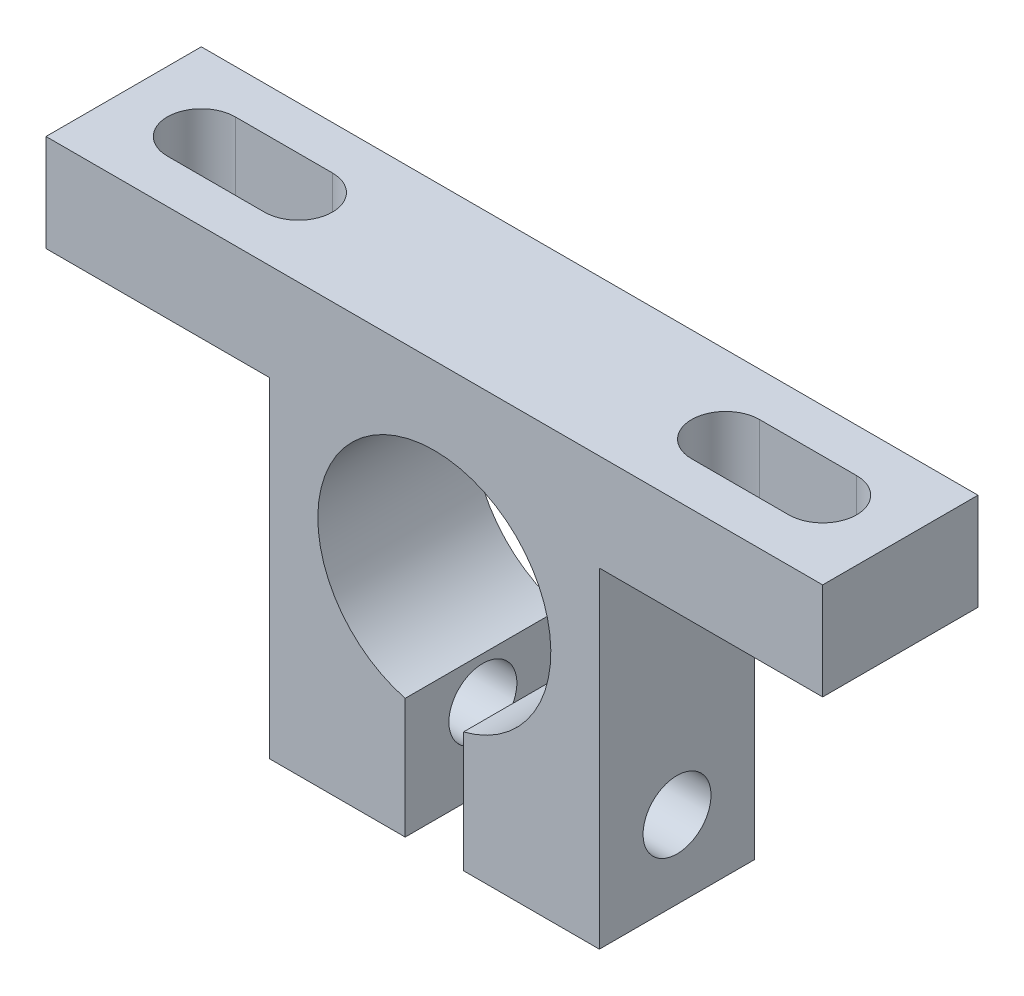
SolidWorks part; units mm, degrees
ref_plane "前视基准面" through (0, 0, 0) normal (0, 0, 1) x (1, 0, 0)
ref_plane "上视基准面" through (0, 0, 0) normal (0, 1, 0) x (1, 0, 0)
ref_plane "右视基准面" through (0, 0, 0) normal (1, 0, 0) x (0, 0, -1)
sketch "草图1" plane through (0, 0, 0) normal (0, 0, 1) x (1, 0, 0)
  line L0 (0, 0) -> (0, 11.4885) construction
  line L1 (34.9259, 10) -> (51.6493, 10) construction
  line L2 (20, 10) -> (-20, 10)
  line L3 (-20, 10) -> (-20, 5)
  line L4 (-20, 5) -> (-8.5, 5)
  line L5 (-8.5, 5) -> (-8.5, -12)
  line L6 (-8.5, -12) -> (-1.5, -12)
  line L7 (-1.5, -12) -> (-1.5, -5.8095)
  line L8 (1.5, -12) -> (1.5, -5.8095)
  line L9 (8.5, -12) -> (1.5, -12)
  line L10 (8.5, 5) -> (8.5, -12)
  line L11 (20, 5) -> (8.5, 5)
  line L12 (20, 10) -> (20, 5)
  arc A0 (1.5, -5.8095) -> (-1.5, -5.8095) centre (0, 0) ccw
  point P4 (0, 10)
  point P10 (0, -12)
  point P12 (-8.5, -12)
  point P16 (-1.5, -12)
  point P23 (0, 10)
  dimension "D1" = 10
  dimension "D5" = 6
  dimension "D2" = 22
  dimension "D3" = 8.5
  dimension "D4" = 1.5
extrude "凸台-拉伸1" add sketch "草图1" along normal blind 8
sketch "草图2" plane through (0, 10, 0) normal (0, 1, 0) x (1, 0, 0)
  line L0 (-20, -4) -> (20, -4) construction
  line L1 (-20, -8) -> (-20, 0) construction
  line L2 (20, -8) -> (20, 0) construction
  line L3 (-16, -2.25) -> (-11, -2.25)
  line L4 (-16, -5.75) -> (-11, -5.75)
  line L5 (0, -4) -> (0, -16.3697) construction
  line L6 (16, -5.75) -> (11, -5.75)
  line L7 (16, -2.25) -> (11, -2.25)
  arc A0 (-11, -5.75) -> (-11, -2.25) centre (-11, -4) ccw
  arc A1 (-16, -2.25) -> (-16, -5.75) centre (-16, -4) ccw
  arc A2 (16, -2.25) -> (16, -5.75) centre (16, -4) cw
  arc A3 (11, -5.75) -> (11, -2.25) centre (11, -4) cw
  point P6 (0, -4)
  point P7 (-11, -4)
  point P10 (-16, -4)
  dimension "D2" = 5
  dimension "D1" = 11
extrude "切除-拉伸1" cut sketch "草图2" against normal blind 8
sketch "草图3" plane through (-8.5, 0, 0) normal (-1, 0, 0) x (0, 0, 1)
  line L0 (4, -12) -> (4, -8) construction
  line L1 (8, -12) -> (0, -12) construction
  circle A0 centre (4, -8) radius 1.75
  point P0 (0, -12)
  point P1 (8, -12)
extrude "切除-拉伸2" cut sketch "草图3" against normal blind 26
